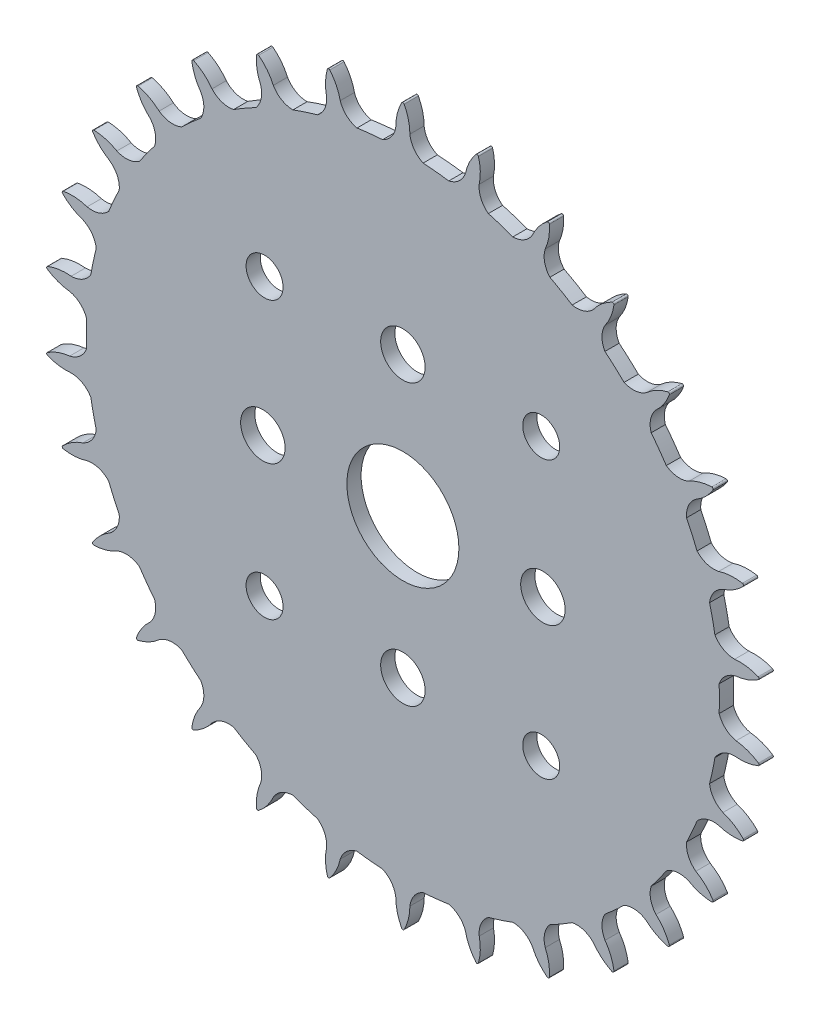
SolidWorks part; units mm, degrees
ref_plane "Front Plane" through (0, 0, 0) normal (0, 0, 1) x (1, 0, 0)
ref_plane "Top Plane" through (0, 0, 0) normal (0, 1, 0) x (1, 0, 0)
ref_plane "Right Plane" through (0, 0, 0) normal (1, 0, 0) x (0, 0, -1)
sketch "Sketch1" plane through (0, 0, 0) normal (0, 0, 1) x (1, 0, 0)
  circle A0 centre (0, 10) radius 1.5875
  circle A1 centre (0, 0) radius 22.6042
  circle A2 centre (9.8783, -9.8783) radius 1.3208
  circle A3 centre (9.8783, 9.8783) radius 1.3208
  circle A4 centre (-9.8783, -9.8783) radius 1.3208
  circle A5 centre (-9.8783, 9.8783) radius 1.3208
  circle A6 centre (0, 0) radius 4
  circle A7 centre (10, 0) radius 1.5875
  circle A8 centre (0, -10) radius 1.5875
  circle A9 centre (-10, 0) radius 1.5875
  dimension "D1" = 4
  dimension "D2" = 4
extrude "Boss-Extrude2" add sketch "Sketch1" along normal blind 1.016
sketch "Sketch2" plane through (0, 0, 1.016) normal (0, 0, 1) x (1, 0, 0)
  arc A0 (0.5, 23.8734) -> (0.0883, 25.5232) centre (-3.0117, 23.8734) ccw
  arc A1 (-0.5, 23.8734) -> (-1.6391, 22.4848) centre (-2.1172, 24.0386) cw
  arc A2 (0.0883, 25.5232) -> (-0.0883, 25.5232) centre (0, 25.4763) ccw
  arc A3 (0.5, 23.8734) -> (1.6391, 22.4848) centre (2.1172, 24.0386) ccw
  arc A4 (-1.6391, 22.4848) -> (1.6391, 22.4848) centre (0, 28.2192) ccw
  arc A5 (-0.5, 23.8734) -> (-0.0883, 25.5232) centre (3.0117, 23.8734) cw
  dimension "D1" = 0.1
extrude "Boss-Extrude4" add sketch "Sketch2" against normal blind 1.016
pattern_circular "CirPattern1" count 30 over 360 about axis through (0, 0, 0) along (0, 0, 1) of "Boss-Extrude4"
